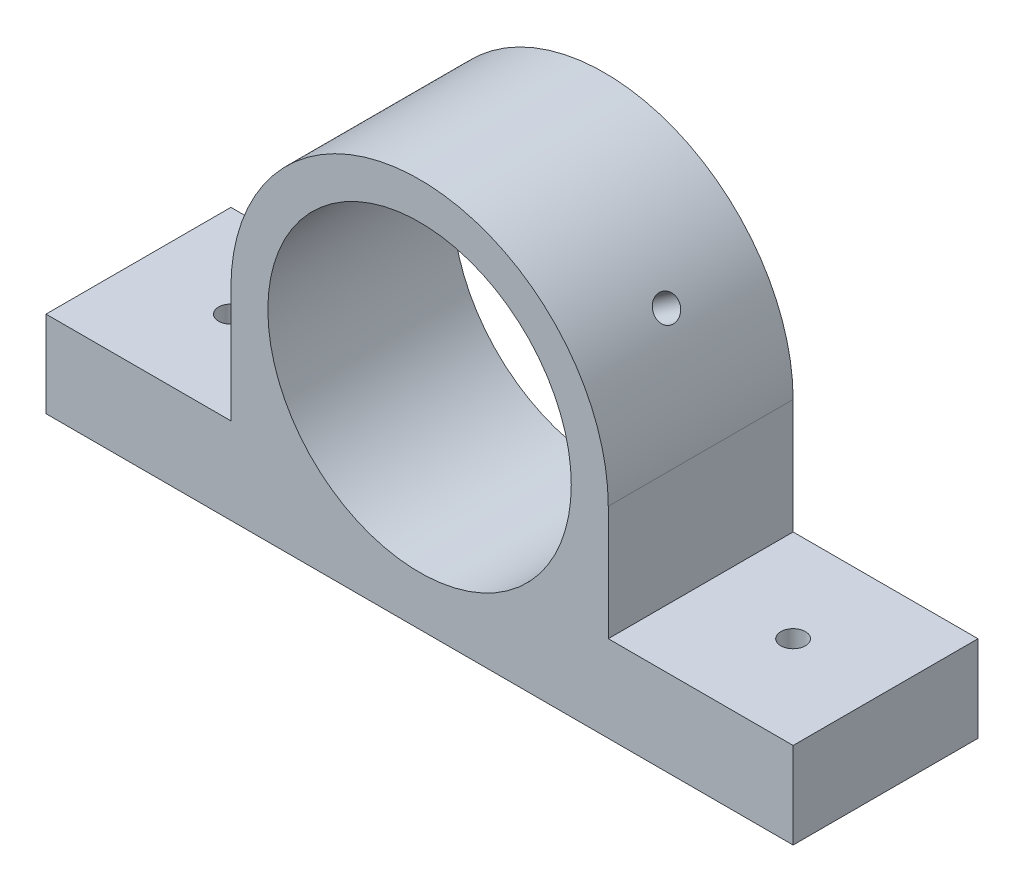
SolidWorks part; units mm, degrees
ref_plane "Front Plane" through (0, 0, 0) normal (0, 0, 1) x (1, 0, 0)
ref_plane "Top Plane" through (0, 0, 0) normal (0, 1, 0) x (1, 0, 0)
ref_plane "Right Plane" through (0, 0, 0) normal (1, 0, 0) x (0, 0, -1)
sketch "Sketch1" plane through (0, 0, 0) normal (0, 0, 1) x (1, 0, 0)
  line L0 (-12.31, 0) -> (-12.31, -12.31)
  line L1 (-12.31, -12.31) -> (-30.31, -12.31)
  line L2 (-30.31, -12.31) -> (-30.31, -9.31)
  line L3 (-30.31, -9.31) -> (-15.31, -9.31)
  line L4 (-15.31, -9.31) -> (-15.31, 0)
  line L6 (12.31, 0) -> (12.31, -12.31)
  line L7 (12.31, -12.31) -> (30.31, -12.31)
  line L8 (30.31, -12.31) -> (30.31, -9.31)
  line L9 (30.31, -9.31) -> (15.31, -9.31)
  line L10 (15.31, -9.31) -> (15.31, 0)
  arc A0 (12.31, 0) -> (-12.31, 0) centre (0, 0) ccw
  arc A1 (15.31, 0) -> (-15.31, 0) centre (0, 0) ccw
  dimension "D1" = 24.62
  dimension "D2" = 3
  dimension "D3" = 3
  dimension "15" = 15
extrude "Boss-Extrude1" add sketch "Sketch1" along normal blind 15
sketch "Sketch3" plane through (0, 0, 15) normal (0, 0, 1) x (1, 0, 0)
  line L0 (30.31, -12.31) -> (30.31, -9.31) construction
  line L1 (-30.31, -12.31) -> (-12.31, -12.31)
  line L2 (-30.31, -12.31) -> (-30.31, -16.31)
  line L3 (-30.31, -16.31) -> (30.31, -16.31)
  line L4 (30.31, -12.31) -> (30.31, -16.31)
  line L5 (-30.31, -9.31) -> (-30.31, -12.31) construction
  line L6 (12.31, 0) -> (12.31, -12.31) construction
  line L7 (-12.31, -12.31) -> (-12.31, 0) construction
  line L8 (-12.31, 0) -> (-12.31, -12.31)
  line L10 (12.31, -12.31) -> (12.31, 0)
  line L11 (12.31, -12.31) -> (30.31, -12.31)
  arc A0 (-12.31, 0) -> (12.31, 0) centre (0, 0) ccw
  dimension "D1" = 4
extrude "Boss-Extrude2" add sketch "Sketch3" against normal blind 15
sketch "Sketch2" plane through (0, -9.31, 0) normal (0, 1, 0) x (1, 0, 0)
  line L0 (22.81, 0) -> (22.81, -15) construction
  line L1 (30.31, 0) -> (15.31, 0) construction
  line L2 (30.31, -15) -> (15.31, -15) construction
  line L3 (-22.81, 0) -> (-22.81, -15) construction
  line L4 (-15.31, 0) -> (-30.31, 0) construction
  line L5 (-15.31, -15) -> (-30.31, -15) construction
  circle A0 centre (22.81, -7.5) radius 1
  circle A1 centre (-22.81, -7.5) radius 1
  dimension "D1" = 2
  dimension "D2" = 2
extrude "Cut-Extrude1" cut sketch "Sketch2" against normal blind 25
sketch "Sketch4" plane through (0, 0, 15) normal (0, 0, 1) x (1, 0, 0)
  line L0 (0, 0) -> (12.5412, 8.7815) construction
  line L1 (0, 0) -> (-12.5412, 8.7815) construction
  line L2 (0, 0) -> (0, 15.31) construction
  arc A0 (15.31, 0) -> (-15.31, 0) centre (0, 0) ccw construction
  dimension "D1" = 55
  dimension "D2" = 55
ref_plane "Plane1" through (12.5412, 8.7815, 0) normal (0.8192, 0.5736, 0) x (0, 0, -1)
sketch "Sketch5" plane through (12.5412, 8.7815, 0) normal (0.8192, 0.5736, 0) x (0, 0, -1)
  line L0 (-15, 0) -> (0, 0) construction
  line L1 (-15, 0) -> (-15, 12.5412) construction
  line L2 (-15, 0) -> (-15, 14.3867) construction
  circle A0 centre (-7.5, 0) radius 1
  dimension "D1" = 2
extrude "Cut-Extrude2" cut sketch "Sketch5" against normal blind 4
ref_plane "Plane2" through (-12.5412, 8.7815, 0) normal (-0.8192, 0.5736, 0) x (0, 0, 1)
sketch "Sketch6" plane through (-12.5412, 8.7815, 0) normal (-0.8192, 0.5736, 0) x (0, 0, 1)
  line L0 (15, 0) -> (0, 0) construction
  line L1 (15, 0) -> (15, 12.5412) construction
  line L2 (15, 0) -> (15, 14.3867) construction
  circle A0 centre (7.5, 0) radius 1
  dimension "D1" = 2
extrude "Cut-Extrude3" cut sketch "Sketch6" against normal blind 4
